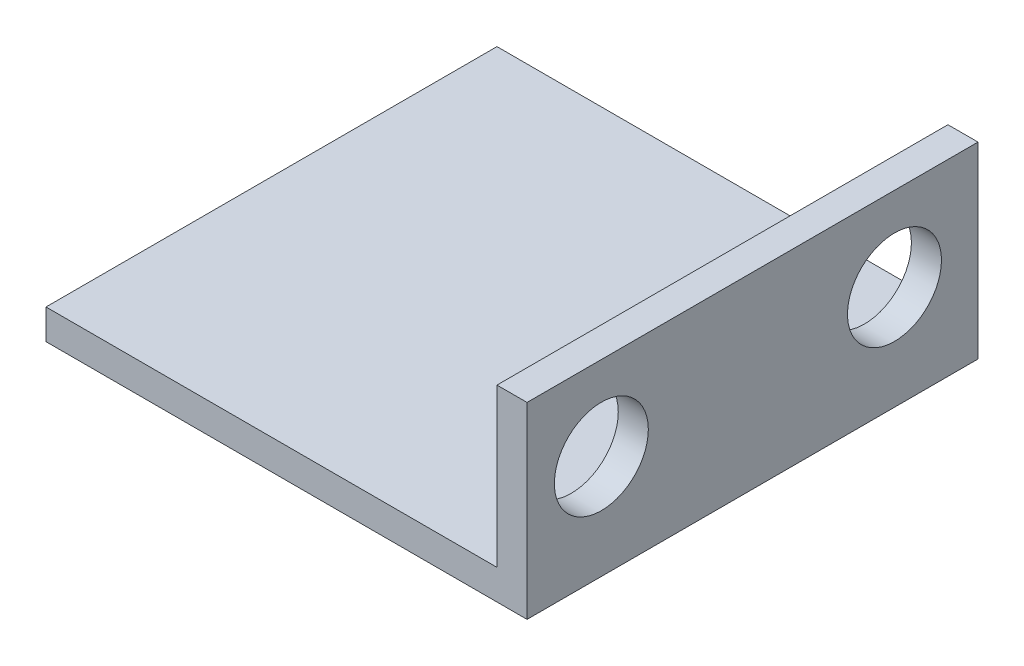
SolidWorks part; units mm, degrees
ref_plane "前视基准面" through (0, 0, 0) normal (0, 0, 1) x (1, 0, 0)
ref_plane "上视基准面" through (0, 0, 0) normal (0, 1, 0) x (1, 0, 0)
ref_plane "右视基准面" through (0, 0, 0) normal (1, 0, 0) x (0, 0, -1)
other "Configuration Table"
sketch "草图1" plane through (0, 0, 0) normal (0, 1, 0) x (1, 0, 0)
  line L1 (-60, 60) -> (60, 60)
  line L2 (-60, 60) -> (-60, -60)
  line L3 (-60, -60) -> (60, -60)
  line L4 (60, 60) -> (60, -60)
  line L5 (-60, 60) -> (60, -60) construction
  line L6 (-60, -60) -> (60, 60) construction
  point P0 (0, 0)
  dimension "170" = 120
  dimension "D2" = 120
extrude "凸台-拉伸1" add sketch "草图1" along normal blind 8
sketch "草图2" plane through (60, 0, 0) normal (1, 0, 0) x (0, 0, -1)
  line L6 (-60, 50) -> (60, 50)
  line L7 (-60, 50) -> (-60, 0)
  line L8 (-60, 0) -> (60, 0)
  line L9 (60, 50) -> (60, 0)
  line L10 (-60, 50) -> (60, 0) construction
  line L11 (-60, 0) -> (60, 50) construction
  point P0 (0, 25)
  dimension "D1" = 120
  dimension "100" = 50
extrude "凸台-拉伸2" add sketch "草图2" along normal blind 8
sketch "草图3" plane through (68, 0, 0) normal (1, 0, 0) x (0, 0, -1)
  circle A0 centre (-40.2219, 27.6678) radius 12.5
  circle A1 centre (37.7781, 27.6658) radius 12.5
  point P4 (-41.5001, 19.3648)
  point P5 (32.5065, 19.3637)
  point P6 (36.5206, 19.3648)
  point P7 (-41.1887, 22.712)
  point P8 (36.9102, 22.712)
  point P9 (36.8771, 27.6658)
  point P10 (-40.2219, 27.6658)
  dimension "D1" = 25
  dimension "D2" = 25
  dimension "D3" = 78
extrude "切除-拉伸1" cut sketch "草图3" against normal blind 8
sketch "草图4" plane through (0, 0, 0) normal (0, -1, 0) x (1, 0, 0)
  circle A0 centre (0, 0) radius 55
  dimension "D1" = 110
extrude "切除-拉伸2" cut sketch "草图4" against normal blind 0.1
